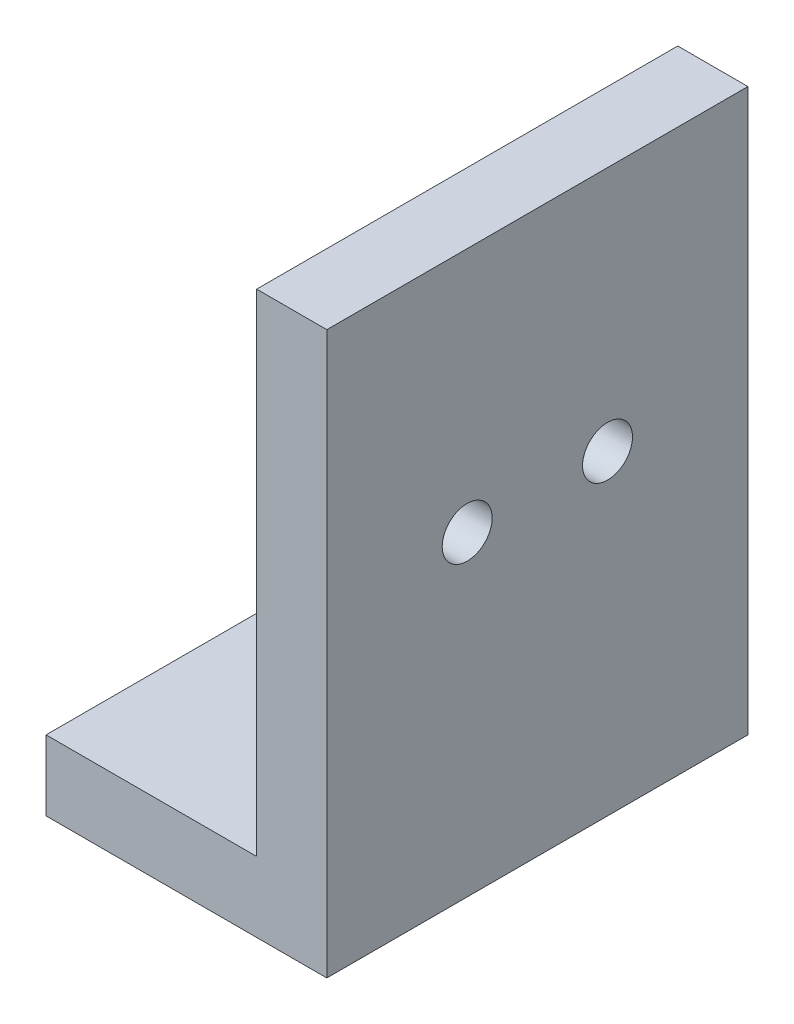
SolidWorks part; units mm, degrees
ref_plane "Front Plane" through (0, 0, 0) normal (0, 0, 1) x (1, 0, 0)
ref_plane "Top Plane" through (0, 0, 0) normal (0, 1, 0) x (1, 0, 0)
ref_plane "Right Plane" through (0, 0, 0) normal (1, 0, 0) x (0, 0, -1)
sketch "Sketch1" plane through (0, 0, 0) normal (0, 0, 1) x (1, 0, 0)
  line L0 (0, 0) -> (12.7, 0)
  line L1 (12.7, 0) -> (12.7, 25.4)
  line L2 (12.7, 25.4) -> (9.525, 25.4)
  line L3 (9.525, 25.4) -> (9.525, 3.175)
  line L4 (9.525, 3.175) -> (0, 3.175)
  line L5 (0, 3.175) -> (0, 0)
  dimension "D1" = 25.4
  dimension "D2" = 12.7
  dimension "D3" = 3.175
  dimension "D4" = 3.175
extrude "Boss-Extrude1" add sketch "Sketch1" along normal blind 19.05 contours L1 L2 L3 L4 L5 L0
hole_wizard "#4-40 Tapped Hole1" positions "Sketch3" profile "Sketch2" tap size "#4-40" standard "ANSI Inch"
sketch "Sketch3" plane through (9.525, 0, 0) normal (-1, 0, 0) x (0, 0, 1)
  line L0 (19.05, 25.4) -> (19.05, 3.175) construction
  line L1 (0, 25.4) -> (0, 3.175) construction
  line L2 (19.05, 3.175) -> (0, 3.175) construction
  point P0 (6.35, 14.2875)
  point P2 (12.7, 14.2875)
  dimension "D1" = 6.35
  dimension "D2" = 6.35
  dimension "D3" = 11.1125
  dimension "D4" = 11.1125
sketch "Sketch2" plane through (9.525, 14.2875, 6.35) normal (0, 1, 0) x (0, 0, 1)
  line L0 (0, 0) -> (0, 8.2738)
  line L1 (0, 8.2738) -> (1.1303, 7.5946)
  line L2 (1.1303, 7.5946) -> (1.1303, 0)
  line L5 (1.1303, 0) -> (0, 0)
  line L10 (0, 8.2738) -> (-1.1303, 7.5946) construction
  line L11 (0, -6.35) -> (0, 107.95) construction
  dimension "Tap Drill Dia." = 2.2606
  dimension "Tap Drill Depth" = 7.5946
  dimension "Drill Angle" = 118
hole_wizard "#4-40 Tapped Hole2" positions "Sketch5" profile "Sketch4" tap size "#4-40" standard "ANSI Inch"
sketch "Sketch5" plane through (0, 3.175, 0) normal (0, 1, 0) x (1, 0, 0)
  line L0 (9.525, -19.05) -> (0, -19.05) construction
  line L1 (9.525, 0) -> (0, 0) construction
  line L2 (0, -19.05) -> (0, 0) construction
  point P0 (4.7625, -6.35)
  point P2 (4.7625, -12.7)
  dimension "D1" = 6.35
  dimension "D2" = 6.35
  dimension "D3" = 4.7625
  dimension "D4" = 4.7625
sketch "Sketch4" plane through (4.7625, 3.175, 6.35) normal (1, 0, 0) x (0, 0, 1)
  line L0 (0, 0) -> (0, 8.2738)
  line L1 (0, 8.2738) -> (1.1303, 7.5946)
  line L2 (1.1303, 7.5946) -> (1.1303, 0)
  line L5 (1.1303, 0) -> (0, 0)
  line L10 (0, 8.2738) -> (-1.1303, 7.5946) construction
  line L11 (0, -6.35) -> (0, 107.95) construction
  dimension "Tap Drill Dia." = 2.2606
  dimension "Tap Drill Depth" = 7.5946
  dimension "Drill Angle" = 118
